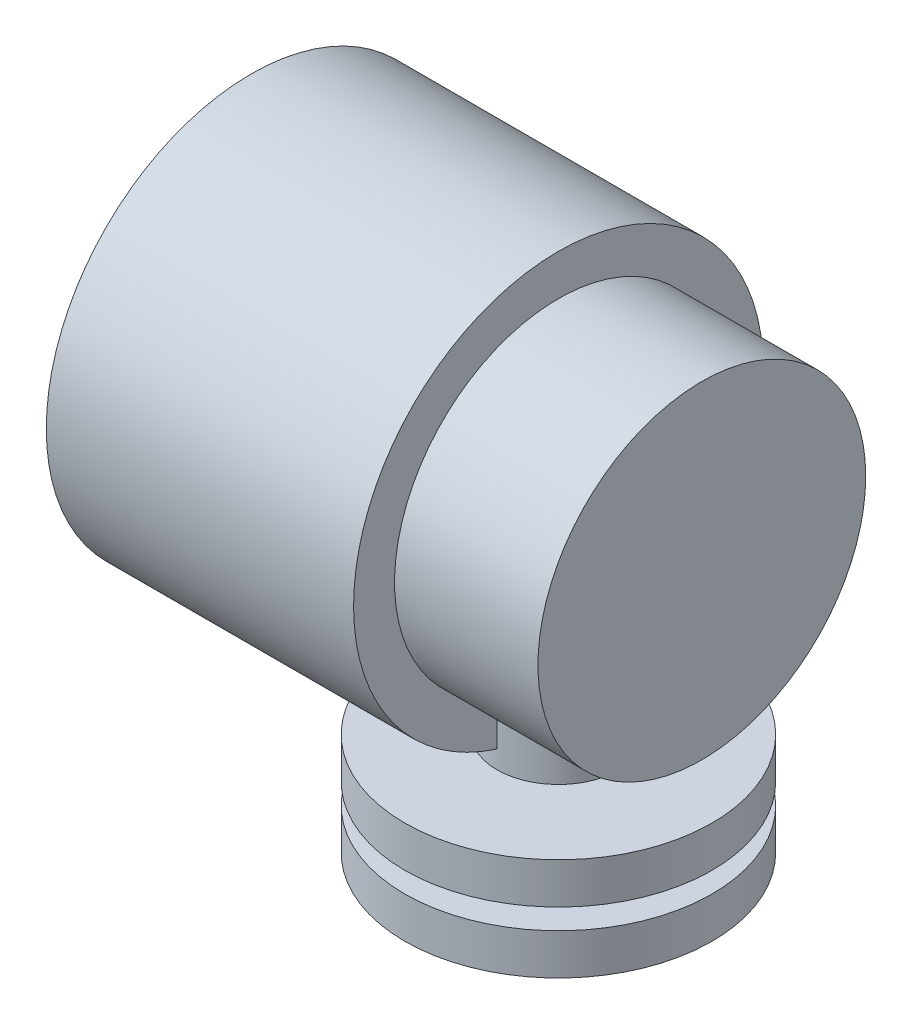
SolidWorks part; units mm, degrees
ref_plane "Front Plane" through (0, 0, 0) normal (0, 0, 1) x (1, 0, 0)
ref_plane "Top Plane" through (0, 0, 0) normal (0, 1, 0) x (1, 0, 0)
ref_plane "Right Plane" through (0, 0, 0) normal (1, 0, 0) x (0, 0, -1)
sketch "Sketch1" plane through (0, 0, 0) normal (0, 1, 0) x (1, 0, 0)
  circle A0 centre (0, 0) radius 75
extrude "Boss-Extrude1" add sketch "Sketch1" along normal blind 20
sketch "Sketch2" plane through (0, 20, 0) normal (0, 1, 0) x (1, 0, 0)
  circle A0 centre (0, 0) radius 60
extrude "Boss-Extrude2" add sketch "Sketch2" along normal blind 10
sketch "Sketch3" plane through (0, 30, 0) normal (0, 1, 0) x (1, 0, 0)
  circle A0 centre (0, 0) radius 75
extrude "Boss-Extrude3" add sketch "Sketch3" along normal blind 20
sketch "Sketch4" plane through (0, 50, 0) normal (0, 1, 0) x (1, 0, 0)
  circle A0 centre (0, 0) radius 30
extrude "Boss-Extrude4" add sketch "Sketch4" along normal blind 100
sketch "Sketch5" plane through (0, 0, 0) normal (1, 0, 0) x (0, 0, -1)
  line L0 (0, 0) -> (0, 154.2018) construction
  circle A0 centre (0, 154.2018) radius 100
extrude "Boss-Extrude5" add sketch "Sketch5" against normal blind 150
sketch "Sketch6" plane through (0, 0, 0) normal (1, 0, 0) x (0, 0, -1)
  circle A0 centre (0, 154.2018) radius 80
extrude "Boss-Extrude6" add sketch "Sketch6" along normal blind 70
